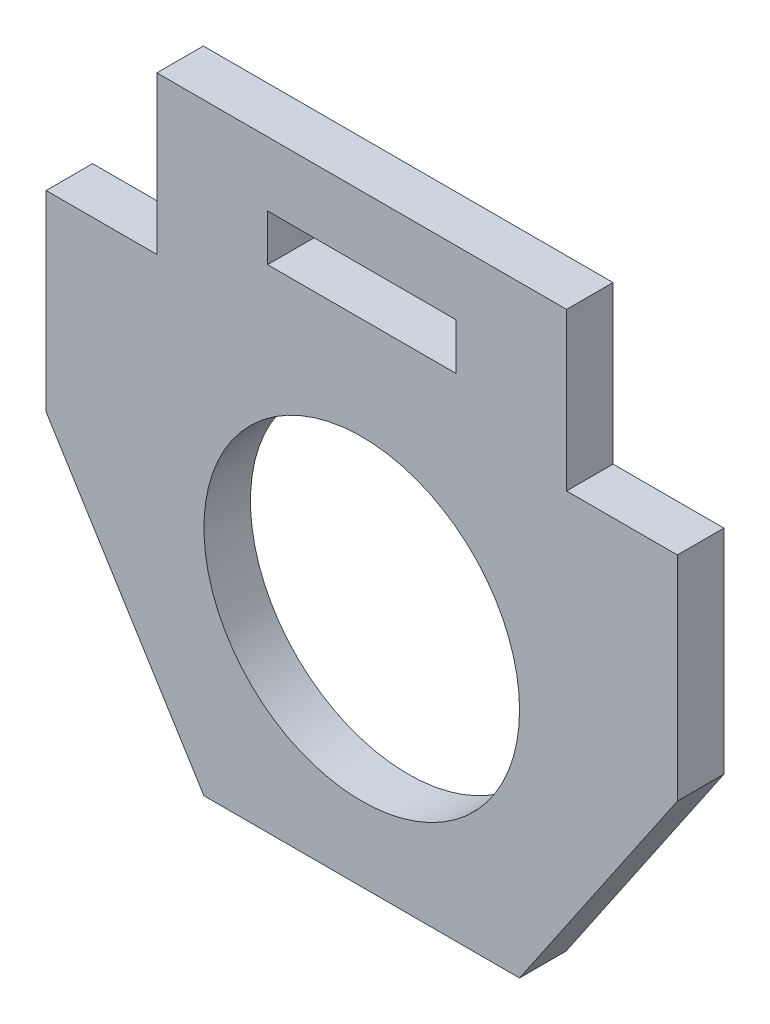
SolidWorks part; units mm, degrees
ref_plane "Front Plane" through (0, 0, 0) normal (0, 0, 1) x (1, 0, 0)
ref_plane "Top Plane" through (0, 0, 0) normal (0, 1, 0) x (1, 0, 0)
ref_plane "Right Plane" through (0, 0, 0) normal (1, 0, 0) x (0, 0, -1)
sketch "Sketch1" plane through (0, 0, 0) normal (0, 0, 1) x (1, 0, 0)
  line L0 (-36.2, 2.4626) -> (0, -26.6191) construction
  line L1 (-36.2, 24.45) -> (-23.5, 24.45)
  line L2 (-36.2, 24.45) -> (-36.2, 2.4626)
  line L3 (-18.1, -26.6191) -> (18.1, -26.6191)
  line L4 (36.2, 24.45) -> (36.2, 0)
  line L5 (-36.2, 24.45) -> (36.2, -24.45) construction
  line L6 (-24.4073, -16.485) -> (36.2, 24.45) construction
  line L7 (0, -26.6191) -> (36.2, 0) construction
  line L8 (-18.1, -12.0782) -> (-18.1, -26.6191) construction
  line L9 (18.1, -13.3095) -> (18.1, -26.6191) construction
  line L10 (-36.2, 2.4626) -> (-18.1, -26.6191) construction
  line L11 (36.2, 0) -> (18.1, -26.6191) construction
  line L12 (-36.2, 2.4626) -> (-18.1, -26.6191)
  line L13 (18.1, -26.6191) -> (36.2, 0)
  line L14 (-36.2, 24.45) -> (-36.2, 34.5878) construction
  line L15 (-36.2, 34.5878) -> (-23.5, 34.5878) construction
  line L16 (23.49, 24.45) -> (36.2, 24.45)
  line L18 (-23.5, 24.45) -> (-23.5, 42.484)
  line L19 (-23.5, 42.484) -> (23.49, 42.484)
  line L20 (23.49, 24.45) -> (23.49, 42.484)
  line L21 (10.79, 24.45) -> (10.79, 29.784) construction
  line L23 (10.79, 29.784) -> (-10.8, 29.784)
  line L24 (10.79, 29.784) -> (10.79, 35.118)
  line L25 (10.79, 35.118) -> (-10.8, 35.118)
  line L26 (-10.8, 29.784) -> (-10.8, 35.118)
  point P0 (0, 0)
  dimension "D2" = 48.9
  dimension "D3" = 12.7
  dimension "D4" = 46.99
  dimension "D5" = 18.034
  dimension "D6" = 5.334
  dimension "D7" = 21.59
  dimension "D8" = 5.334
  dimension "D9" = 5.334
extrude "Boss-Extrude1" add sketch "Sketch1" along normal blind 5.334
sketch "Sketch2" plane through (0, 0, 5.334) normal (0, 0, 1) x (1, 0, 0)
  circle A0 centre (0, 0) radius 18.1
  dimension "D1" = 36.2
extrude "Cut-Extrude1" cut sketch "Sketch2" against normal blind 5.334
